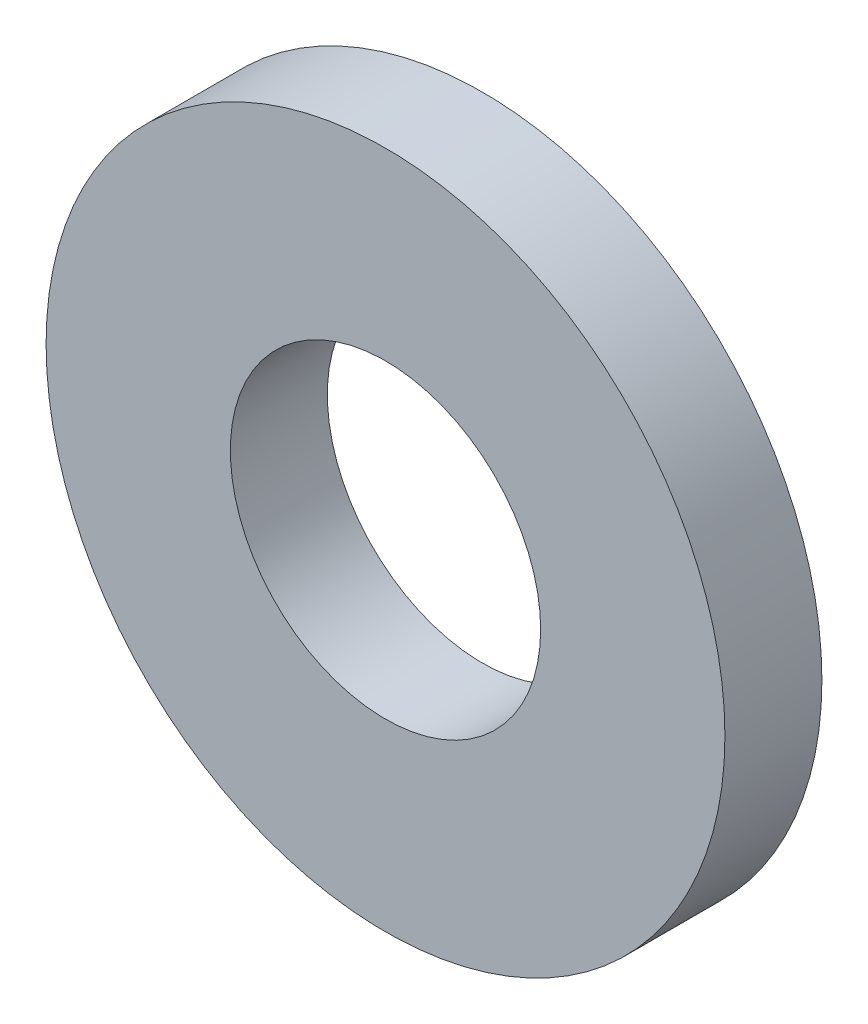
SolidWorks part; units mm, degrees
ref_plane "前视基准面" through (0, 0, 0) normal (0, 0, 1) x (1, 0, 0)
ref_plane "上视基准面" through (0, 0, 0) normal (0, 1, 0) x (1, 0, 0)
ref_plane "右视基准面" through (0, 0, 0) normal (1, 0, 0) x (0, 0, -1)
sketch "尺寸草图" plane through (0, 0, 0) normal (0, 0, 1) x (1, 0, 0)
  line L0 (0, 0) -> (0.5, 0) construction
  circle A0 centre (0, 0) radius 3.5
  circle A1 centre (0, 0) radius 1.6
  dimension "d2" = 7
  dimension "d1" = 3.2
  dimension "h" = 0.5
extrude "拉伸1" add sketch "尺寸草图" along normal blind 1
